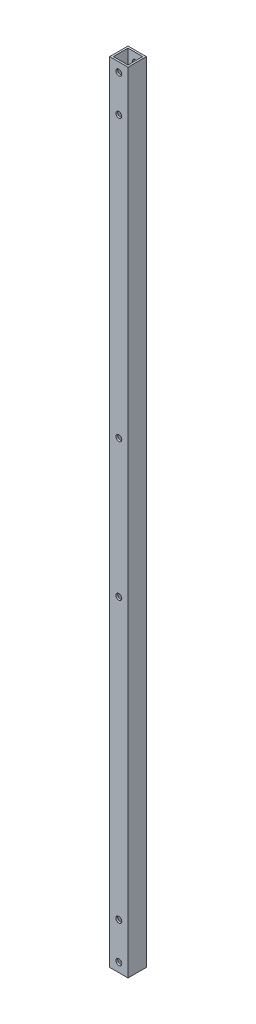
SolidWorks part; units mm, degrees
ref_plane "正面" through (0, 0, 0) normal (0, 0, 1) x (1, 0, 0)
ref_plane "平面" through (0, 0, 0) normal (0, 1, 0) x (1, 0, 0)
ref_plane "右側面" through (0, 0, 0) normal (1, 0, 0) x (0, 0, -1)
sketch "ｽｹｯﾁ1" plane through (0, 0, 0) normal (0, 1, 0) x (1, 0, 0)
  line L0 (-4, 4) -> (4, 4)
  line L1 (-5, 5) -> (5, 5)
  line L2 (-5, 5) -> (-5, -5)
  line L3 (-5, -5) -> (5, -5)
  line L4 (5, 5) -> (5, -5)
  line L5 (-5, 5) -> (5, -5) construction
  line L6 (-5, -5) -> (5, 5) construction
  line L7 (4, 4) -> (4, -4)
  line L8 (-4, -4) -> (4, -4)
  line L9 (-4, 4) -> (-4, -4)
  point P0 (0, 0)
  dimension "D1" = 10
  dimension "D2" = 1
extrude "ﾎﾞｽ - 押し出し1" add sketch "ｽｹｯﾁ1" along normal mid plane 429.94
sketch "ｽｹｯﾁ2" plane through (0, 0, 5) normal (0, 0, 1) x (1, 0, 0)
  line L0 (0, 214.97) -> (0, 209.97) construction
  line L1 (-5, 214.97) -> (5, 214.97) construction
  line L2 (0, 209.97) -> (0, 189.97) construction
  circle A0 centre (0, 209.97) radius 1.6
  circle A1 centre (0, 189.97) radius 1.6
  dimension "D3" = 3.2
  dimension "D4" = 3.2
  dimension "D1" = 5
  dimension "D2" = 20
extrude "ｶｯﾄ - 押し出し1" cut sketch "ｽｹｯﾁ2" against normal mid plane 427.43
mirror "ﾐﾗｰ1" about plane through (0, 0, 0) normal (0, 1, 0) of "ｶｯﾄ - 押し出し1"
sketch "ｽｹｯﾁ3" plane through (0, 0, -5) normal (0, 0, -1) x (-1, 0, 0)
  circle A0 centre (0, -37.5797) radius 1.6 construction
  circle A1 centre (-0.005, 37.4203) radius 1.6 construction
  circle A2 centre (0, -37.5797) radius 1.6
  circle A3 centre (-0.005, 37.4203) radius 1.6
extrude "ｶｯﾄ - 押し出し2" cut sketch "ｽｹｯﾁ3" against normal blind 10
